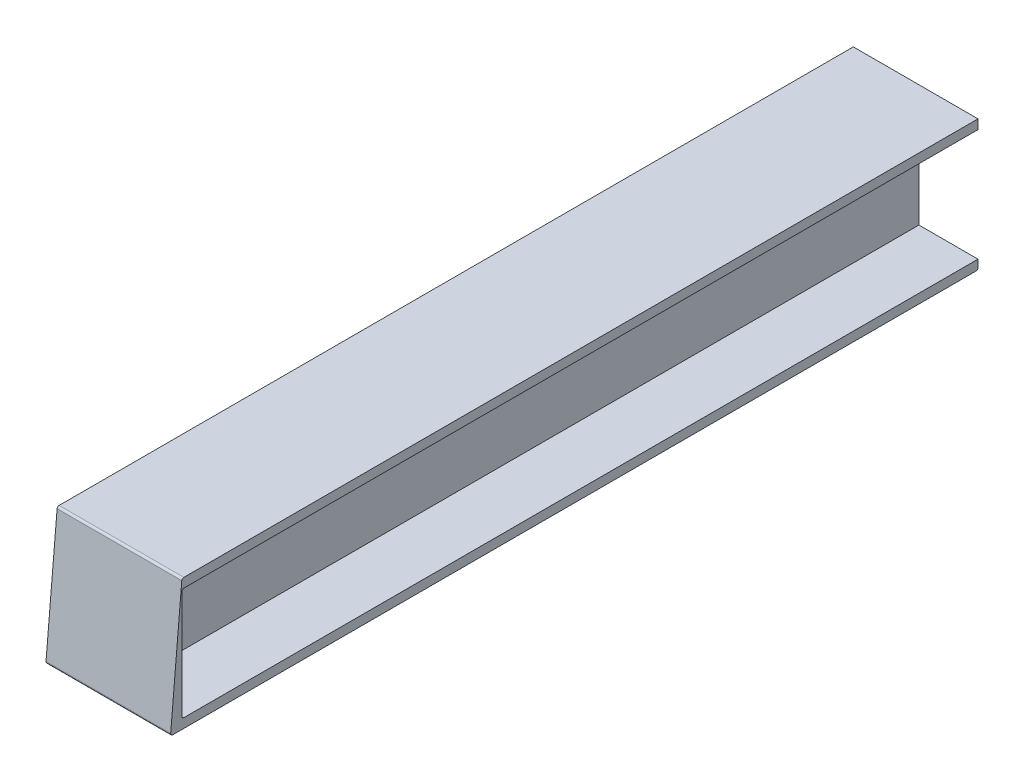
SolidWorks part; units mm, degrees
material "ASTM A992 Steel"
ref_plane "Front" through (0, 0, 0) normal (0, 0, 1) x (1, 0, 0)
ref_plane "Top" through (0, 0, 0) normal (0, 1, 0) x (1, 0, 0)
ref_plane "Right" through (0, 0, 0) normal (1, 0, 0) x (0, 0, -1)
sketch "Sketch1" plane through (0, 0, 0) normal (0, 0, 1) x (1, 0, 0)
  line L0 (0, -0.0002) -> (154.432, -0.0002)
  line L1 (154.432, -0.0002) -> (154.432, -11.5572)
  line L2 (154.432, -11.5572) -> (81.28, -11.5572)
  line L3 (81.28, -11.5572) -> (81.28, -150.4952)
  line L4 (81.28, -150.4952) -> (154.432, -150.4952)
  line L5 (154.432, -150.4952) -> (154.432, -162.0522)
  line L6 (154.432, -162.0522) -> (0, -162.0522)
  line L7 (0, -162.0522) -> (0, -150.4952)
  line L8 (0, -150.4952) -> (73.152, -150.4952)
  line L9 (73.152, -150.4952) -> (73.152, -11.5572)
  line L10 (73.152, -11.5572) -> (0, -11.5572)
  line L11 (0, -11.5572) -> (0, -0.0002)
  line L12 (77.216, -0.0002) -> (77.216, -162.0522) construction
  point P15 (154.432, -156.2737)
  dimension "D1" = 8.128
  dimension "D2" = 11.557
  dimension "D3" = 11.557
  dimension "D4" = 11.557
  dimension "D5" = 162.052
  dimension "D6" = 4.064
  dimension "D7" = 77.216
  dimension "D8" = 77.216
extrude "Boss-Extrude1" add sketch "Sketch1" along normal blind 900
sketch "Sketch4" plane through (154.432, 0, 0) normal (1, 0, 0) x (0, 0, -1)
  line L0 (-900, -0.0002) -> (-914.1777, -162.0522)
  line L1 (-900, -150.4952) -> (-900, -11.5572) construction
  line L2 (-900, -162.0522) -> (-914.1777, -162.0522)
  line L3 (-900, -0.0002) -> (-900, -162.0522)
  dimension "D1" = 5
extrude "Boss-Extrude7" add sketch "Sketch4" against normal up to surface (154.432 mm away) contours L2 L0 L3 up to face at (0, -156.2737, 450)
sketch "Sketch6" plane through (0, 0, 0) normal (0, 0, -1) x (-1, 0, 0)
  line L12 (0, -11.5572) -> (0, -0.0002)
  line L13 (0, -0.0002) -> (-154.432, -0.0002)
  line L14 (-154.432, -0.0002) -> (-154.432, -11.5572)
  line L15 (-154.432, -11.5572) -> (-81.28, -11.5572)
  line L16 (-81.28, -11.5572) -> (-81.28, -150.4952)
  line L17 (-81.28, -150.4952) -> (-154.432, -150.4952)
  line L18 (-154.432, -150.4952) -> (-154.432, -162.0522)
  line L19 (-154.432, -162.0522) -> (0, -162.0522)
  line L20 (0, -162.0522) -> (0, -150.4952)
  line L21 (0, -150.4952) -> (-73.152, -150.4952)
  line L22 (-73.152, -150.4952) -> (-73.152, -11.5572)
  line L23 (-73.152, -11.5572) -> (0, -11.5572)
  line L24 (0, -11.5572) -> (0, -0.0002)
  line L25 (0, -0.0002) -> (-154.432, -0.0002)
  line L26 (-154.432, -0.0002) -> (-154.432, -11.5572)
  line L27 (-154.432, -11.5572) -> (-81.28, -11.5572)
  line L28 (-81.28, -11.5572) -> (-81.28, -150.4952)
  line L29 (-81.28, -150.4952) -> (-154.432, -150.4952)
  line L30 (-154.432, -150.4952) -> (-154.432, -162.0522)
  line L31 (-154.432, -162.0522) -> (0, -162.0522)
  line L32 (0, -162.0522) -> (0, -150.4952)
  line L33 (0, -150.4952) -> (-73.152, -150.4952)
  line L34 (-73.152, -150.4952) -> (-73.152, -11.5572)
  line L35 (-73.152, -11.5572) -> (0, -11.5572)
  dimension "D1" = 0
extrude "Boss-Extrude9" add sketch "Sketch6" along normal up to surface (86.0123 mm away)
fillet "Fillet1" radius 2.54 6 edges at (117.856, -11.5572, 900) (117.856, -150.4952, 900) (77.216, -0.0002, 900) (36.576, -11.5572, 900) (36.576, -150.4952, 900) (77.216, -162.0522, 914.1777)
fillet "Fillet2" radius 2.54 1 edges at (77.216, -162.0522, -86.0123)
